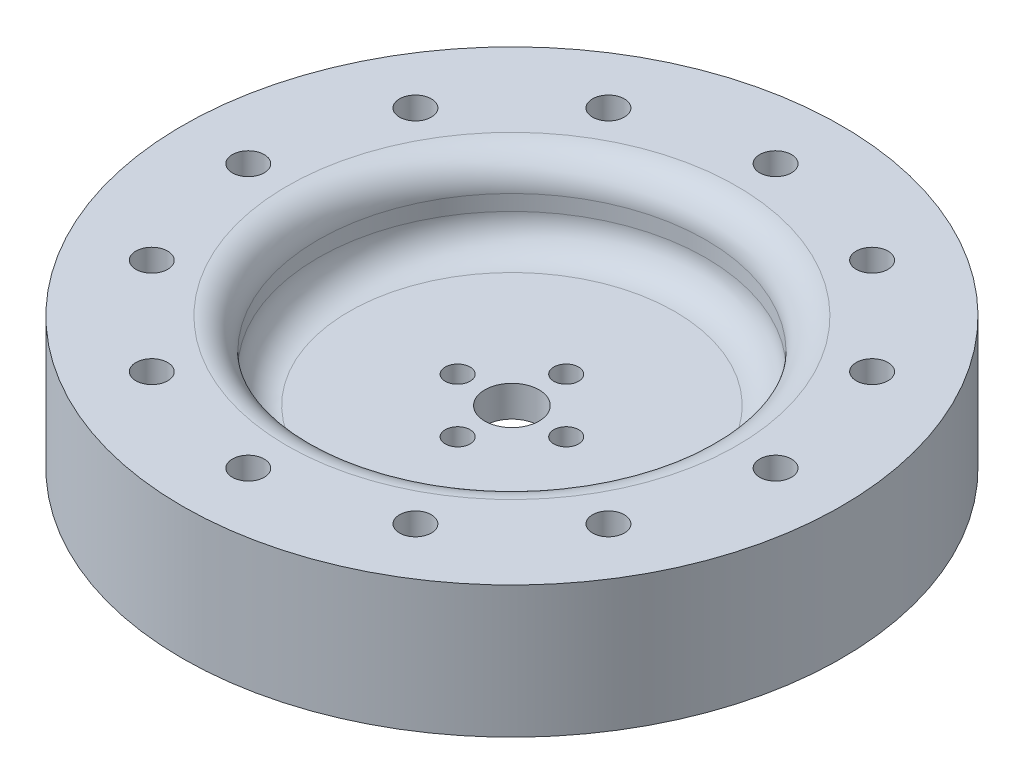
SolidWorks part; units mm, degrees
ref_plane "前视基准面" through (0, 0, 0) normal (0, 0, 1) x (1, 0, 0)
ref_plane "上视基准面" through (0, 0, 0) normal (0, 1, 0) x (1, 0, 0)
ref_plane "右视基准面" through (0, 0, 0) normal (1, 0, 0) x (0, 0, -1)
sketch "草图1" plane through (0, 0, 0) normal (0, 1, 0) x (1, 0, 0)
  circle A0 centre (0, 0) radius 42.5
  circle A1 centre (34, 0) radius 2.05
  circle A2 centre (29.4449, -17) radius 2.05
  circle A3 centre (17, -29.4449) radius 2.05
  circle A4 centre (0, -34) radius 2.05
  circle A5 centre (-17, -29.4449) radius 2.05
  circle A6 centre (-29.4449, -17) radius 2.05
  circle A7 centre (-34, 0) radius 2.05
  circle A8 centre (-29.4449, 17) radius 2.05
  circle A9 centre (-17, 29.4449) radius 2.05
  circle A10 centre (0, 34) radius 2.05
  circle A11 centre (17, 29.4449) radius 2.05
  circle A12 centre (29.4449, 17) radius 2.05
  circle A13 centre (7, 0) radius 1.6
  circle A14 centre (0, -7) radius 1.6
  circle A15 centre (-7, 0) radius 1.6
  circle A16 centre (0, 7) radius 1.6
  circle A17 centre (0, 0) radius 3.5
  point P30 (0, 0)
  point P39 (0, 0)
  dimension "D1" = 85
  dimension "D2" = 4.1
  dimension "D4" = 12
  dimension "D6" = 3.2
  dimension "D7" = 4
  dimension "D8" = 7
  dimension "D3" = 34
  dimension "D5" = 7
extrude "凸台-拉伸1" add sketch "草图1" along normal blind 17
sketch "草图2" plane through (0, 17, 0) normal (0, 1, 0) x (1, 0, 0)
  circle A0 centre (0, 0) radius 25
  dimension "D1" = 50
extrude "切除-拉伸1" cut sketch "草图2" against normal blind 10
fillet "圆角1" radius 4 2 edges at (0, 17, 25) (0, 7, 25)
sketch "草图3" plane through (0, 0, 0) normal (0, -1, 0) x (1, 0, 0)
  circle A0 centre (0, 0) radius 12
  dimension "D1" = 24
extrude "切除-拉伸2" cut sketch "草图3" against normal blind 3
